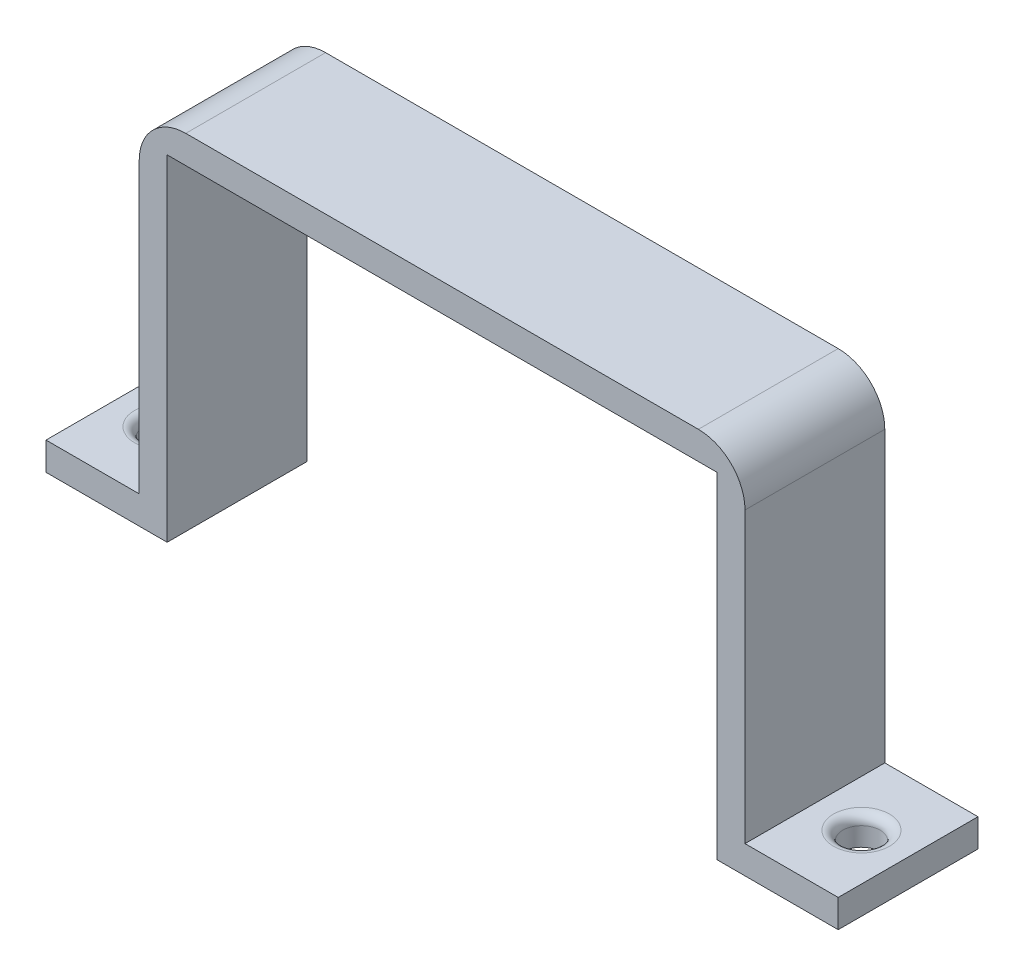
SolidWorks part; units mm, degrees
ref_plane "Front Plane" through (0, 0, 0) normal (0, 0, 1) x (1, 0, 0)
ref_plane "Top Plane" through (0, 0, 0) normal (0, 1, 0) x (1, 0, 0)
ref_plane "Right Plane" through (0, 0, 0) normal (1, 0, 0) x (0, 0, -1)
sketch "Sketch2" plane through (0, 0, 0) normal (0, 1, 0) x (1, 0, 0)
  line L0 (0, 0) -> (32.5, 0)
  line L1 (-55, 0) -> (55, 0) construction
  line L2 (0, 0) -> (-32.5, 0)
  line L3 (-32.5, 0) -> (-32.5, 7.5)
  line L5 (32.5, -7.5) -> (-32.5, -7.5)
  line L6 (32.5, -7.5) -> (32.5, 7.5)
  line L7 (32.5, 7.5) -> (-32.5, 7.5)
  line L8 (-32.5, -7.5) -> (-32.5, 7.5)
  line L9 (32.5, -7.5) -> (-32.5, 7.5) construction
  line L10 (32.5, 7.5) -> (-32.5, -7.5) construction
extrude "Boss-Extrude1" add sketch "Sketch2" along normal blind 3 contours L8 L5 L6 L0 L2 | L6 L7 L3 L2 L0
sketch "Sketch3" plane through (0, 0, 0) normal (0, -1, 0) x (1, 0, 0)
  line L0 (-32.5, 7.5) -> (-29.5, 7.5)
  line L1 (32.5, 7.5) -> (-32.5, 7.5) construction
  line L2 (-29.5, 7.5) -> (-32.5, -7.5)
  line L3 (-32.5, -7.5) -> (-29.5, -7.5)
  line L4 (-29.5, -7.5) -> (-29.5, 7.5)
  line L5 (-32.5, 7.5) -> (-32.5, -7.5)
  line L6 (32.5, 7.5) -> (29.5, 7.5)
  line L7 (29.5, 7.5) -> (29.5, -7.5)
  line L8 (32.5, -7.5) -> (-32.5, -7.5) construction
  line L9 (29.5, -7.5) -> (32.5, -7.5)
  line L10 (32.5, -7.5) -> (32.5, 7.5)
  line M3 (-32.5, 7.5) -> (-32.5, -7.5)
  line M4 (-32.5, -7.5) -> (32.5, -7.5)
  line M5 (32.5, -7.5) -> (32.5, 7.5)
  line M6 (32.5, 7.5) -> (-32.5, 7.5)
extrude "Boss-Extrude2" add sketch "Sketch3" along normal blind 36 contours L2 M6 M3 | L4 L2 M4 | L7 M6 M4 M5
sketch "Sketch5" plane through (32.5, 0, 0) normal (1, 0, 0) x (0, 0, -1)
  line L0 (-7.5, -36) -> (-7.5, -33)
  line L1 (-7.5, 3) -> (-7.5, -36) construction
  line L2 (-7.5, -33) -> (7.5, -33)
  line L3 (7.5, 3) -> (7.5, -36) construction
  line L4 (7.5, -33) -> (7.5, -36)
  line L5 (7.5, -36) -> (-7.5, -36)
extrude "Boss-Extrude3" add sketch "Sketch5" along normal blind 10
sketch "Sketch6" plane through (-32.5, 0, 0) normal (-1, 0, 0) x (0, 0, 1)
  line L0 (-7.5, -36) -> (-7.5, -33)
  line L1 (-7.5, 3) -> (-7.5, -36) construction
  line L2 (-7.5, -33) -> (7.5, -33)
  line L3 (7.5, 3) -> (7.5, -36) construction
  line L4 (7.5, -33) -> (7.5, -36)
  line L5 (7.5, -36) -> (-7.5, -36)
extrude "Boss-Extrude4" add sketch "Sketch6" along normal blind 10
sketch "Sketch7" plane through (0, -33, 0) normal (0, 1, 0) x (1, 0, 0)
  line L0 (-42.5, 7.5) -> (-32.5, -7.5)
  line L1 (42.5, -7.5) -> (32.5, 7.5)
  circle A0 centre (-37.5, 0) radius 2
  circle A1 centre (37.5, 0) radius 2
extrude "Cut-Extrude1" cut sketch "Sketch7" against normal blind 3 contours L0 A0 | L0 A0 | L1 A1 | L1 A1
fillet "Fillet1" radius 5 2 edges at (32.5, 3, 0) (-32.5, 3, 0)
fillet "Fillet2" radius 1 2 edges at (-37.5, -33, 2) (37.5, -33, 2)
